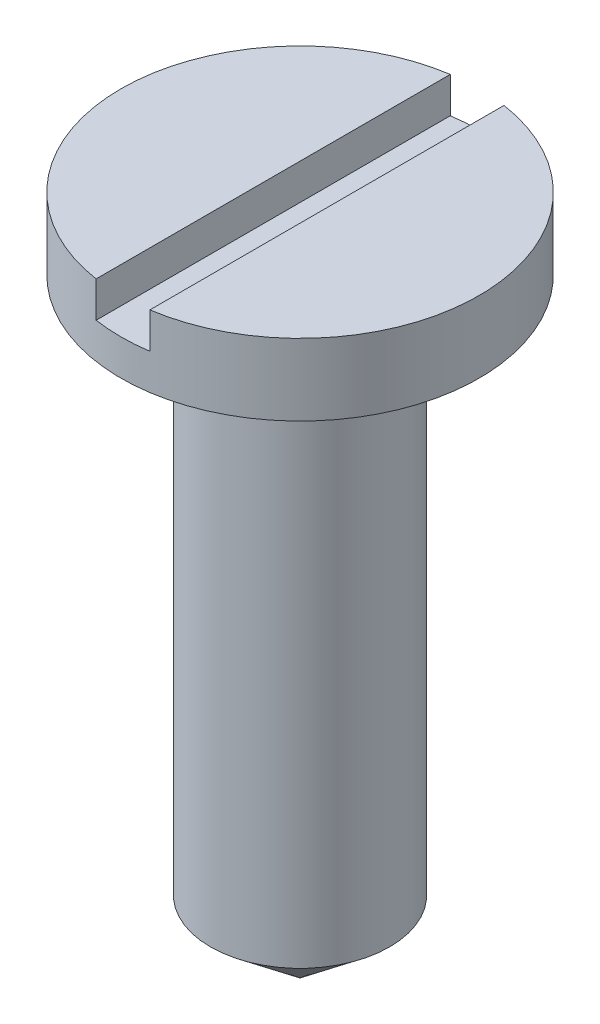
SolidWorks part; units mm, degrees
ref_plane "Front Plane" through (0, 0, 0) normal (0, 0, 1) x (1, 0, 0)
ref_plane "Top Plane" through (0, 0, 0) normal (0, 1, 0) x (1, 0, 0)
ref_plane "Right Plane" through (0, 0, 0) normal (1, 0, 0) x (0, 0, -1)
sketch "Sketch1" plane through (0, 0, 0) normal (0, 0, 1) x (1, 0, 0)
  line L0 (0, 0) -> (0, 15)
  line L1 (0, 15) -> (2.5, 15)
  line L2 (2.5, 15) -> (2.5, 17)
  line L3 (2.5, 17) -> (-2.5, 17)
  line L4 (-2.5, 17) -> (-2.5, 0)
  line L5 (-2.5, 0) -> (0, 0)
  dimension "D1" = 5
  dimension "D2" = 15
  dimension "D3" = 2
  dimension "D4" = 2.5
revolve "Revolve1" add sketch "Sketch1" angle 360 about L4
sketch "Sketch2" plane through (0, 0, 0) normal (0, 0, 1) x (1, 0, 0)
  line L0 (-3.25, 17) -> (-3.25, 16)
  line L1 (2.5, 17) -> (-7.5, 17) construction
  line L2 (-3.25, 16) -> (-1.75, 16)
  line L3 (-1.75, 16) -> (-1.75, 17)
  line L4 (-1.75, 17) -> (-3.25, 17)
  line L5 (-2.5, 0) -> (-2.5, 17)
  line L7 (-5, 0) -> (0, 0) construction
  line L8 (-7.5, 17) -> (2.5, 17)
  dimension "D1" = 1.5
  dimension "D2" = 1
extrude "Cut-Extrude1" cut sketch "Sketch2" against normal through all both and the other way through all contours L0 L2 L3 L4
sketch "Sketch3" plane through (0, 0, 0) normal (0, 0, 1) x (1, 0, 0)
  line L0 (-2.5, 0) -> (-2.5, -2)
  line L1 (-5, 0) -> (0, 0) construction
  line L2 (-2.5, -2) -> (0, 0)
  line L3 (0, 0) -> (-2.5, 0)
  dimension "D1" = 2
revolve "Revolve2" add sketch "Sketch3" angle 360 about L0
